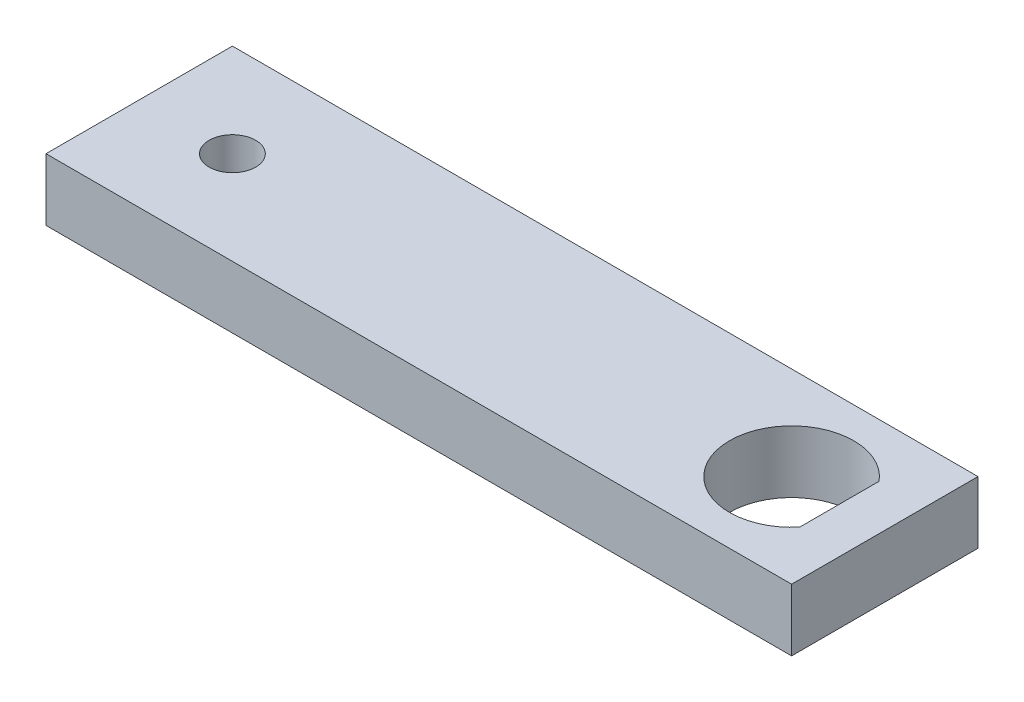
SolidWorks part; units mm, degrees
ref_plane "Front" through (0, 0, 0) normal (0, 0, 1) x (1, 0, 0)
ref_plane "Top" through (0, 0, 0) normal (0, 1, 0) x (-1, 0, 0)
ref_plane "Right" through (0, 0, 0) normal (1, 0, 0) x (0, 0, -1)
other "Configuration Table"
sketch "Sketch1" plane through (0, 0, 0) normal (0, 0, 1) x (1, 0, 0)
  line L0 (0, 0) -> (76.2, 0)
  line L1 (0, 0) -> (0, 6.35)
  line L2 (76.2, 6.35) -> (0, 6.35)
  line L3 (76.2, 6.35) -> (76.2, 0)
  dimension "D1" = 6.35
  dimension "D2" = 76.2
extrude "Base-Extrude" add sketch "Sketch1" along normal blind 19.05
sketch "Sketch2" plane through (0, 6.35, 0) normal (0, 1, 0) x (-1, 0, 0)
  line L0 (-76.2, 19.05) -> (-76.2, 0) construction
  line L1 (-76.2, 19.05) -> (0, 19.05) construction
  line L2 (-71.5645, 5.4734) -> (-71.5645, 13.5766)
  arc A0 (-71.5645, 5.4734) -> (-71.5645, 13.5766) centre (-66.675, 9.525) ccw
  dimension "D1" = 12.7
  dimension "D2" = 9.525
  dimension "D3" = 9.525
  dimension "D4" = 4.8895
extrude "Cut-Extrude1" cut sketch "Sketch2" against normal through all
sketch "Sketch3" plane through (0, 6.35, 0) normal (0, 1, 0) x (-1, 0, 0)
  line L0 (0, 19.05) -> (0, 0) construction
  circle A0 centre (-9.525, 9.525) radius 2.3813
  arc A1 (-71.5645, 5.4734) -> (-71.5645, 13.5766) centre (-66.675, 9.525) ccw construction
  point P5 (-66.675, 9.525)
  dimension "D1" = 4.7625
  dimension "D2" = 9.525
extrude "Cut-Extrude2" cut sketch "Sketch3" against normal through all
